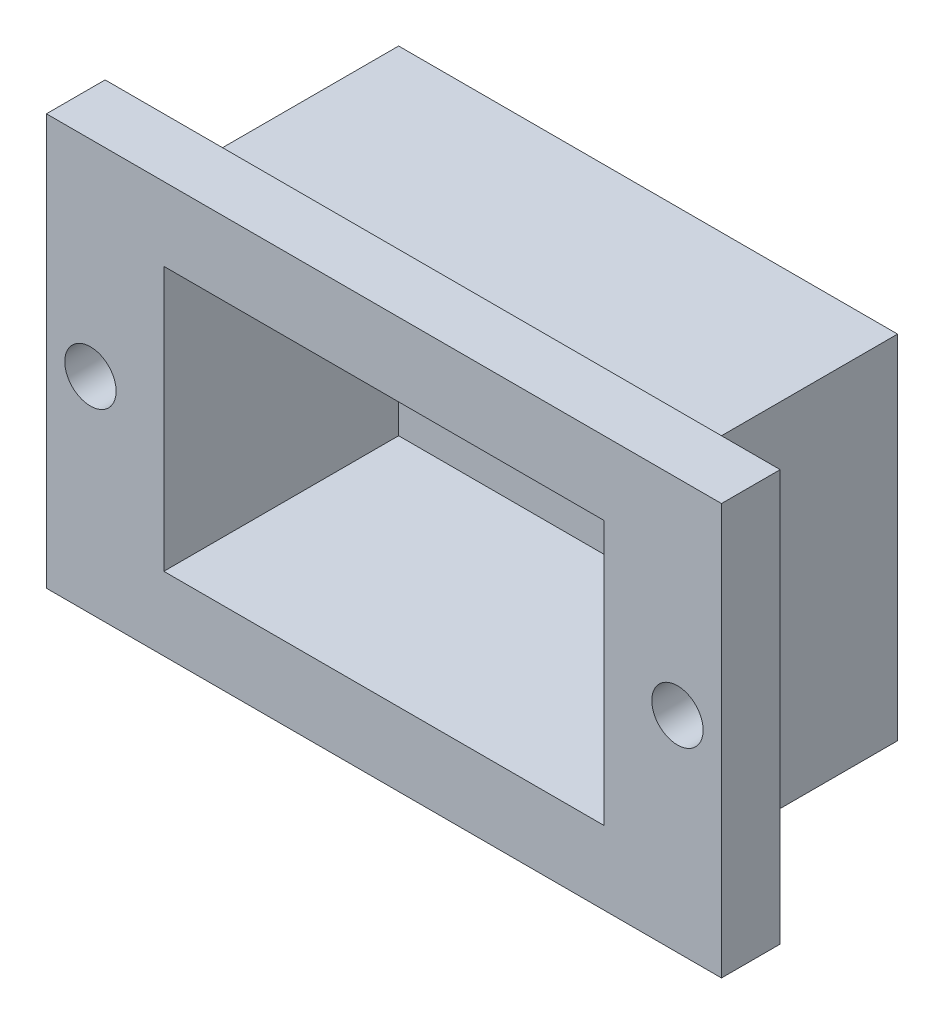
SolidWorks part; units mm, degrees
ref_plane "Alzado" through (0, 0, 0) normal (0, 0, 1) x (1, 0, 0)
ref_plane "Planta" through (0, 0, 0) normal (0, 1, 0) x (1, 0, 0)
ref_plane "Vista lateral" through (0, 0, 0) normal (1, 0, 0) x (0, 0, -1)
sketch "Croquis1" plane through (0, 0, 0) normal (0, 0, 1) x (1, 0, 0)
  line L1 (-23, 14) -> (23, 14)
  line L2 (-23, 14) -> (-23, -14)
  line L3 (-23, -14) -> (23, -14)
  line L4 (23, 14) -> (23, -14)
  dimension "D1" = 46
  dimension "D2" = 23
  dimension "D3" = 28
  dimension "D4" = 14
extrude "Saliente-Extruir1" add sketch "Croquis1" along normal blind 2
sketch "Croquis2" plane through (0, 0, 2) normal (0, 0, 1) x (1, 0, 0)
  line L0 (-23, 14) -> (23, 14)
  line L1 (23, 14) -> (23, -14)
  line L2 (23, -14) -> (-23, -14)
  line L3 (-23, -14) -> (-23, 14)
  line L4 (-15, 9) -> (-15, -9)
  line L5 (-15, -9) -> (15, -9)
  line L6 (15, -9) -> (15, 9)
  line L7 (15, 9) -> (-15, 9)
  dimension "D1" = 30
  dimension "D2" = 15
  dimension "D3" = 18
  dimension "D4" = 5
extrude "Saliente-Extruir2" add sketch "Croquis2" along normal blind 16
sketch "Croquis3" plane through (0, 0, 0) normal (0, 0, -1) x (-1, 0, 0)
  line L0 (-23, 0) -> (23, 0) construction
  line L1 (-23, -14) -> (-23, 14) construction
  line L2 (23, 14) -> (23, -14) construction
  circle A2 centre (-20, 0) radius 1.75
  circle A3 centre (20, 0) radius 1.75
  dimension "D1" = 3.5
  dimension "D2" = 3.5
  dimension "4mm" = 3
  dimension "D4" = 3
extrude "Agujeros" cut sketch "Croquis3" against normal blind 18
sketch "Croquis5" plane through (0, -14, 0) normal (0, -1, 0) x (1, 0, 0)
  line L0 (-23, 14) -> (-17, 14)
  line L1 (-23, 18) -> (-23, 0) construction
  line L2 (-17, 14) -> (-17, 0)
  line L3 (-23, 0) -> (23, 0) construction
  line L4 (-17, 0) -> (-23, 0)
  line L5 (-23, 0) -> (-23, 14)
  line L6 (23, 0) -> (17, 0)
  line L7 (17, 0) -> (17, 14)
  line L8 (17, 14) -> (23, 14)
  line L9 (23, 18) -> (23, 0) construction
  line L10 (23, 14) -> (23, 0)
  dimension "D1" = 6
  dimension "D2" = 6
  dimension "D3" = 14
  dimension "D4" = 14
extrude "Cortar bordes" cut sketch "Croquis5" along direction (0, -1, 0) on the side against the normal through all
sketch "Croquis6" plane through (17, 0, 0) normal (1, 0, 0) x (0, 0, -1)
  line L0 (-14, 14) -> (0, 14)
  line L1 (0, 14) -> (0, 12)
  line L2 (0, 14) -> (0, -14) construction
  line L3 (0, 12) -> (-14, 12)
  line L4 (-14, 14) -> (-14, -14) construction
  line L5 (-14, 12) -> (-14, 14)
  line L6 (0, -14) -> (-14, -14)
  line L7 (-14, -14) -> (-14, -12)
  line L8 (-14, -12) -> (0, -12)
  line L9 (0, -12) -> (0, -14)
  dimension "D1" = 2
  dimension "D2" = 2
extrude "Cortar-Extruir3" cut sketch "Croquis6" against normal through all
